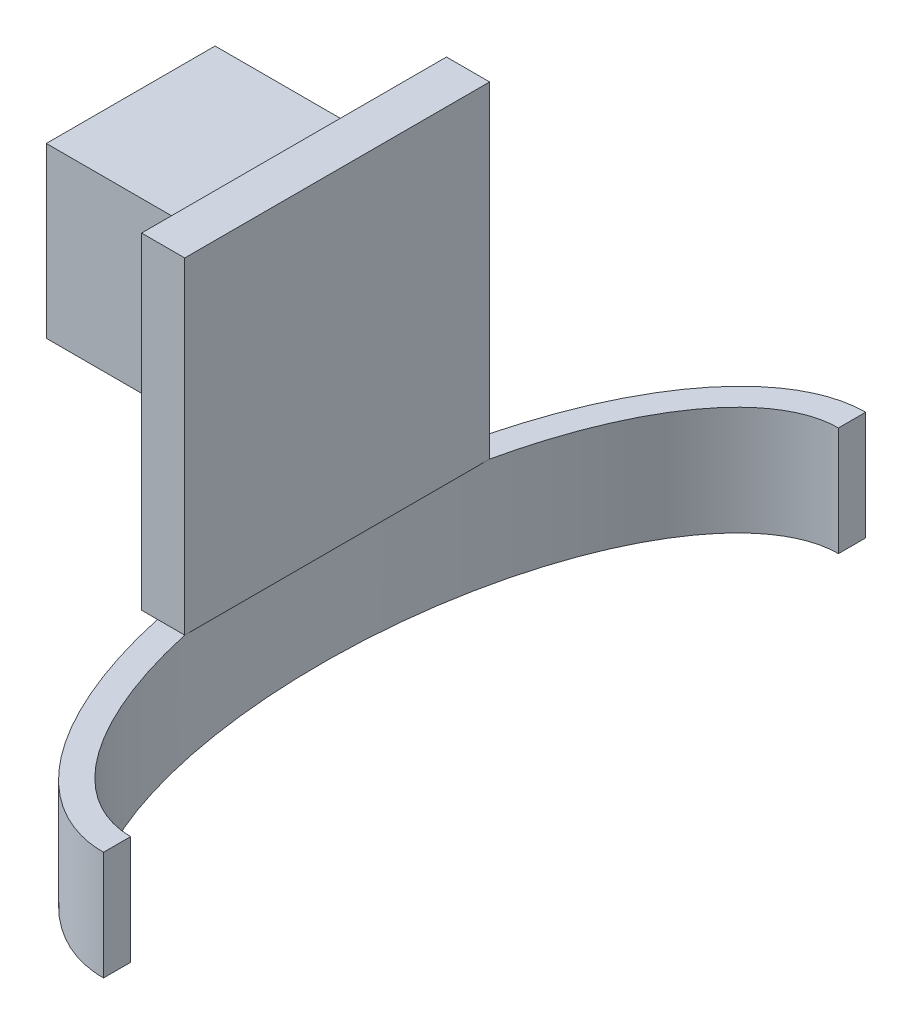
SolidWorks part; units mm, degrees
ref_plane "Front Plane" through (0, 0, 0) normal (0, 0, 1) x (1, 0, 0)
ref_plane "Top Plane" through (0, 0, 0) normal (0, 1, 0) x (1, 0, 0)
ref_plane "Right Plane" through (0, 0, 0) normal (1, 0, 0) x (0, 0, -1)
sketch "Sketch1" plane through (0, 0, 0) normal (0, 1, 0) x (1, 0, 0)
  line L0 (0, -7) -> (0, -6.5)
  line L1 (0, 7) -> (0, 6.5)
  ellipse E0 centre (0, 0) end of major axis (0, -7) minor radius 3.5 (0, 7) -> (0, -7) ccw
  ellipse E1 centre (0, 0) end of major axis (0, -7) minor radius 3.5 (0, 7) -> (0, -7) ccw
  ellipse E2 centre (0, 0) end of major axis (0, 6.5) minor radius 3 (0, 6.5) -> (0, -6.5) ccw
  dimension "D1" = 14
  dimension "D2" = 7
  dimension "D3" = 6
  dimension "D4" = 13
extrude "Boss-Extrude1" add sketch "Sketch1" along normal blind 2 contours E2 L1 E0 L0
sketch "Sketch2" plane through (0, 2, 0) normal (0, 1, 0) x (1, 0, 0)
  line L0 (-3.5, -2.8) -> (-3.5, 2.8)
  line L1 (-3.5, 2.8) -> (-2.7074, 2.8)
  line L2 (-2.7074, 2.8) -> (-2.7074, -2.8)
  line L3 (-2.7074, -2.8) -> (-3.5, -2.8)
  ellipse E1 centre (0, 0) end of major axis (0, 6.5) minor radius 3 (0, 6.5) -> (0, -6.5) ccw construction
  ellipse E2 centre (0, 0) end of major axis (0, -7) minor radius 3.5 (0, 7) -> (0, -7) ccw construction
  point P3 (-3.5489, 0.49)
  point P4 (-2.9935, -0.4286)
  point P5 (-3.5, 0)
  point P10 (-3.5, 0)
  point P19 (-3.4919, 0.4759)
  dimension "D1" = 5.6
extrude "Boss-Extrude2" add sketch "Sketch2" along normal blind 6
sketch "Sketch3" plane through (-3.5, 0, 0) normal (-1, 0, 0) x (0, 0, 1)
  line L0 (0, 8) -> (0, 2) construction
  line L1 (-1.55, 7.3) -> (1.55, 7.3)
  line L2 (-1.55, 7.3) -> (-1.55, 4.2)
  line L3 (-1.55, 4.2) -> (1.55, 4.2)
  line L4 (1.55, 7.3) -> (1.55, 4.2)
  line L5 (0, 7.3) -> (0, 4.2) construction
  line L6 (-2.8, 8) -> (2.8, 8) construction
  line L7 (0, 2) -> (2.8, 2) construction
  dimension "D1" = 2.2
  dimension "D2" = 3.1
extrude "Boss-Extrude3" add sketch "Sketch3" along normal blind 3
